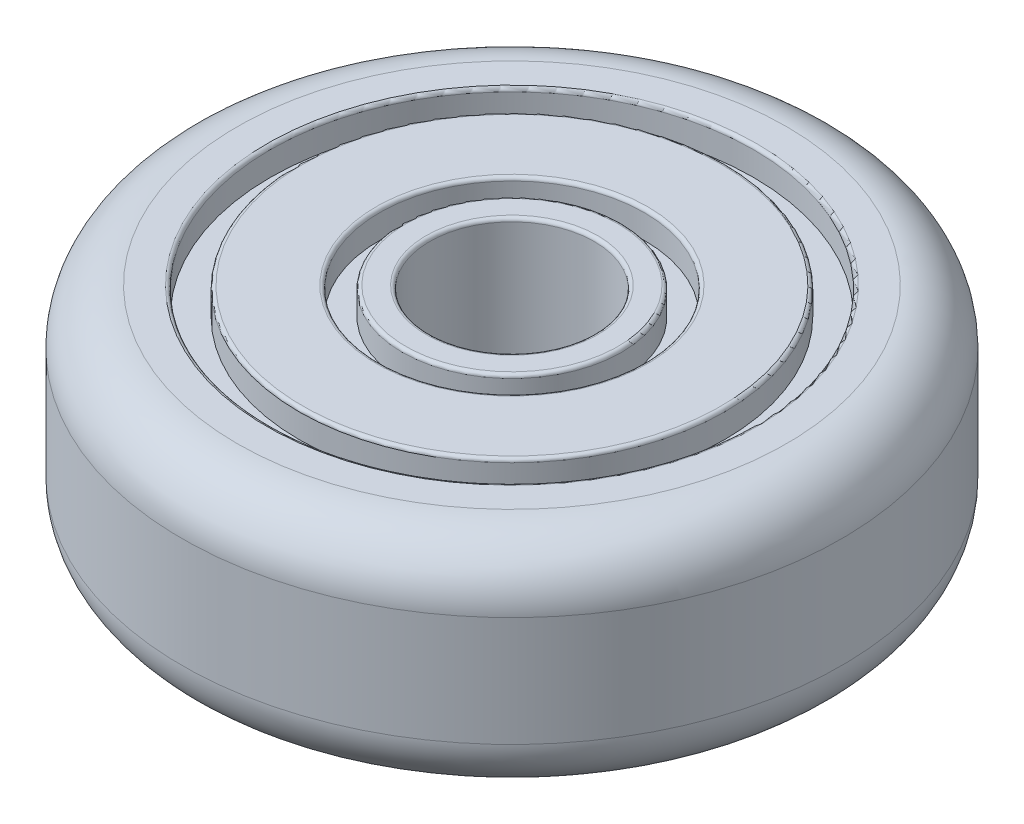
SolidWorks part; units mm, degrees
ref_plane "Front Plane" through (0, 0, 0) normal (0, 0, 1) x (1, 0, 0)
ref_plane "Top Plane" through (0, 0, 0) normal (0, 1, 0) x (1, 0, 0)
ref_plane "Right Plane" through (0, 0, 0) normal (1, 0, 0) x (0, 0, -1)
sketch "Sketch1" plane through (0, 0, 0) normal (0, 1, 0) x (1, 0, 0)
  circle A0 centre (0, 0) radius 12
  circle A1 centre (0, 0) radius 3
  dimension "D1" = 24
  dimension "D2" = 6
extrude "Boss-Extrude1" add sketch "Sketch1" along normal blind 8
fillet "Fillet1" radius 2 2 edges at (0, 0, 12) (0, 8, 12)
sketch "Sketch3" plane through (0, 8, 0) normal (0, 1, 0) x (1, 0, 0)
  circle A0 centre (0, 0) radius 8.7957
  circle A1 centre (0, 0) radius 7.7455
  circle A2 centre (0, 0) radius 4.8221
  circle A3 centre (0, 0) radius 3.9908
extrude "Cut-Extrude1" cut sketch "Sketch3" against normal blind 1 contours A0 A1 | A2 A3
ref_plane "Plane1" through (0, 4, 0) normal (0, 1, 0) x (1, 0, 0)
mirror "Mirror1" about plane through (0, 4, 0) normal (0, 1, 0) of "Cut-Extrude1"
fillet "Fillet2" radius 0.125 5 edges at (0, 8, 8.7957) (0, 8, 3) (0, 8, 3.9908) (0, 8, 4.8221) (0, 8, 7.7455)
move or copy body "Body-Move/Copy1" bodies to move or copy 103
